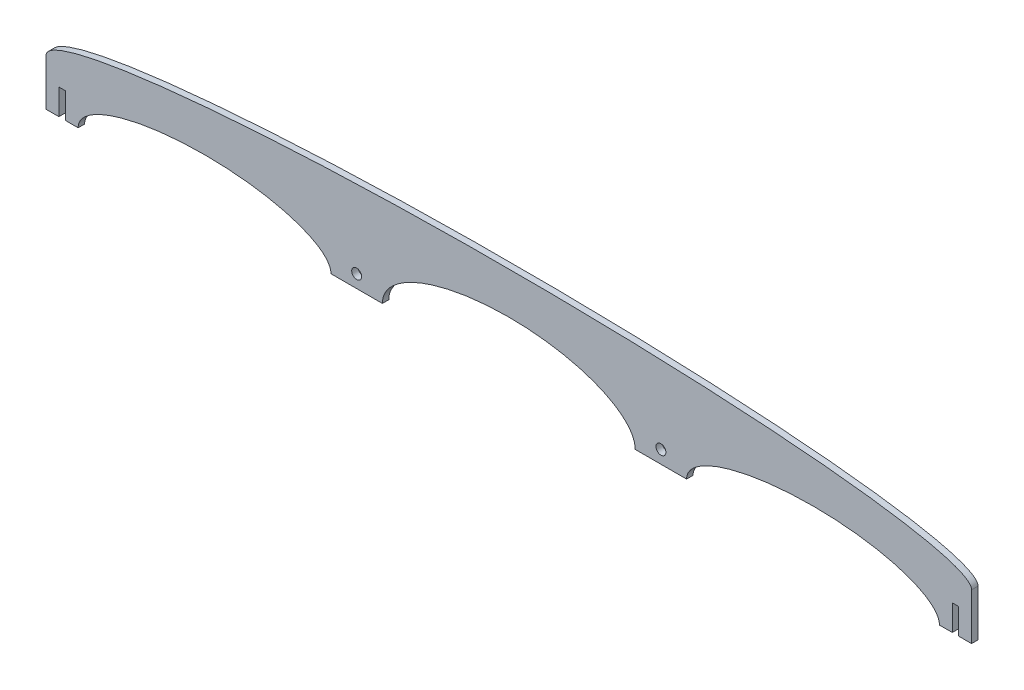
SolidWorks part; units mm, degrees
material "6061 Alloy"
ref_plane "Front Plane" through (0, 0, 0) normal (0, 0, 1) x (1, 0, 0)
ref_plane "Top Plane" through (0, 0, 0) normal (0, 1, 0) x (1, 0, 0)
ref_plane "Right Plane" through (0, 0, 0) normal (1, 0, 0) x (0, 0, -1)
sketch "Sketch1" plane through (0, 0, 0) normal (0, 0, 1) x (1, 0, 0)
  line L0 (-228.6, 0) -> (-228.6, -23.0187)
  line L1 (228.6, 0) -> (228.6, -23.0187)
  line L2 (-228.6, -23.0187) -> (-222.25, -23.0187)
  line L3 (-222.25, -23.0187) -> (-222.25, -10.3187)
  line L4 (-222.25, -10.3187) -> (-219.075, -10.3187)
  line L5 (-219.075, -10.3187) -> (-219.075, -23.0187)
  line L6 (-219.075, -23.0187) -> (-212.725, -23.0187)
  line L7 (-87.8417, -23.0187) -> (-62.4417, -23.0187)
  line L8 (62.4417, -23.0187) -> (87.8417, -23.0187)
  line L9 (228.6, -23.0187) -> (222.25, -23.0187)
  line L10 (222.25, -23.0187) -> (222.25, -10.3187)
  line L11 (222.25, -10.3187) -> (219.075, -10.3187)
  line L12 (219.075, -10.3187) -> (219.075, -23.0187)
  line L13 (219.075, -23.0187) -> (212.725, -23.0187)
  line L14 (-212.725, -23.0187) -> (-87.8417, -23.0187) construction
  line L15 (-62.4417, -23.0187) -> (62.4417, -23.0187) construction
  line L16 (87.8417, -23.0187) -> (212.725, -23.0187) construction
  ellipse E0 centre (0, 0) end of major axis (228.6, 0) minor radius 23.0187 (228.6, 0) -> (-228.6, 0) ccw
  ellipse E1 centre (-150.2833, -23.0187) end of major axis (-87.8417, -23.0187) minor radius 19.7267 (-87.8417, -23.0187) -> (-212.725, -23.0187) ccw
  ellipse E2 centre (0, -23.0187) end of major axis (-62.4417, -23.0187) minor radius 25.4 (62.4417, -23.0187) -> (-62.4417, -23.0187) ccw
  ellipse E3 centre (150.2833, -23.0187) end of major axis (212.725, -23.0187) minor radius 19.7267 (212.725, -23.0187) -> (87.8417, -23.0187) ccw
  point P28 (150.2833, 17.3454)
  dimension "D1" = 46.0375
  dimension "D2" = 457.2
  dimension "D3" = 3.175
  dimension "D4" = 6.35
  dimension "D5" = 12.7
  dimension "D6" = 25.4
  dimension "D7" = 25.4
  dimension "D8" = 20.6375
extrude "Boss-Extrude1" add sketch "Sketch1" along normal blind 3.175
hole_wizard "#10 (0.1935) Diameter Hole1" positions "Sketch2" profile "Sketch3" hole size "#10" standard "ANSI Inch"
sketch "Sketch2" plane through (0, 0, 3.175) normal (0, 0, 1) x (1, 0, 0)
  line L0 (-87.8417, -23.0188) -> (-62.4417, -23.0187) construction
  line L1 (62.4417, -23.0188) -> (87.8417, -23.0187) construction
  point P0 (-75.1417, -16.6688)
  point P2 (75.1417, -16.6687)
  point P7 (-75.1417, -23.0188)
  point P10 (75.1417, -23.0187)
  dimension "D1" = 6.35
sketch "Sketch3" plane through (-75.1417, -16.6688, 3.175) normal (1, 0, 0) x (0, -1, 0)
  line L0 (0, 0) -> (0, 20.4786)
  line L1 (0, 20.4786) -> (2.4574, 19.002)
  line L2 (2.4574, 19.002) -> (2.4574, 0)
  line L5 (2.4574, 0) -> (0, 0)
  line L10 (0, 20.4786) -> (-2.4575, 19.002) construction
  line L11 (0, -6.35) -> (0, 107.95) construction
  dimension "Hole Dia." = 4.9149
  dimension "Hole Depth" = 19.002
  dimension "Drill Angle" = 118
